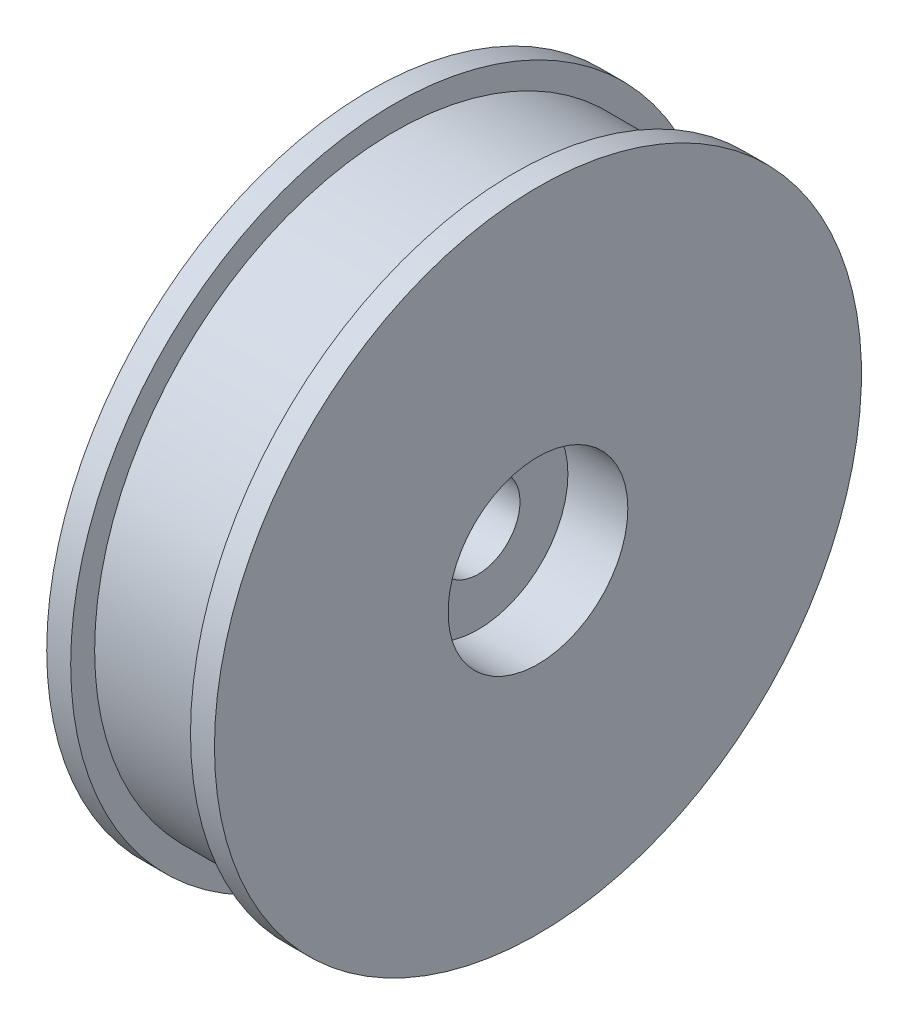
SolidWorks part; units mm, degrees
material "Cast Alloy Steel"
ref_plane "Front Plane" through (0, 0, 0) normal (0, 0, 1) x (1, 0, 0)
ref_plane "Top Plane" through (0, 0, 0) normal (0, 1, 0) x (1, 0, 0)
ref_plane "Right Plane" through (0, 0, 0) normal (1, 0, 0) x (0, 0, -1)
sketch "Sketch1" plane through (0, 0, 0) normal (0, 0, 1) x (1, 0, 0)
  line L0 (-9.5, 0) -> (9.5, 0)
  line L1 (9.5, 0) -> (9.5, 27)
  line L2 (9.5, 27) -> (7.5, 27)
  line L3 (7.5, 27) -> (7.5, 25)
  line L4 (7.5, 25) -> (-2.5, 25)
  line L5 (-2.5, 25) -> (-2.5, 27)
  line L6 (-2.5, 27) -> (-4.5, 27)
  line L7 (-4.5, 27) -> (-4.5, 5)
  line L8 (-4.5, 5) -> (-9.5, 5)
  line L9 (-9.5, 5) -> (-9.5, 0)
  point P0 (0, 0)
  point P11 (0, 0)
  point P13 (0, 0)
  dimension "D2" = 2
  dimension "D3" = 10
  dimension "D4" = 27
  dimension "D5" = 25
  dimension "D6" = 5
  dimension "D7" = 5
revolve "Revolve1" add sketch "Sketch1" angle 360 about L0
sketch "Sketch2" plane through (0, 0, 0) normal (1, 0, 0) x (0, 0, -1)
  circle A0 centre (0, 0) radius 3.5
  dimension "D1" = 7
extrude "Cut-Extrude1" cut sketch "Sketch2" against normal through all both and the other way through all
sketch "Sketch3" plane through (9.5, 0, 0) normal (1, 0, 0) x (0, 0, -1)
  circle A0 centre (0, 0) radius 7.5
  dimension "D1" = 15
extrude "Cut-Extrude2" cut sketch "Sketch3" against normal blind 5
